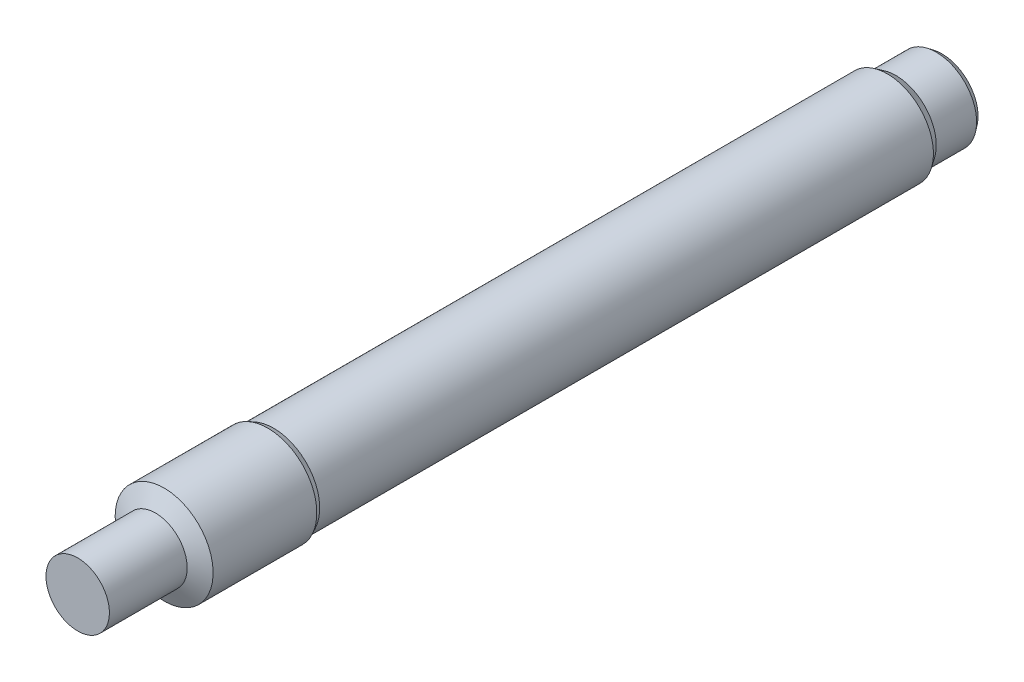
SolidWorks part; units mm, degrees
material "POM Acetal Copolymer"
ref_plane "Front Plane" through (0, 0, 0) normal (0, 0, 1) x (1, 0, 0)
ref_plane "Top Plane" through (0, 0, 0) normal (0, 1, 0) x (1, 0, 0)
ref_plane "Right Plane" through (0, 0, 0) normal (1, 0, 0) x (0, 0, -1)
sketch "Revolve profile 1" plane through (0, 0, 0) normal (0, 1, 0) x (1, 0, 0)
  line L0 (0, -300) -> (0, 0)
  line L1 (0, 0) -> (12.5, 0)
  line L2 (12.5, 0) -> (14, -2)
  line L3 (14, -2) -> (14, -16)
  line L4 (14, -16) -> (16, -19)
  line L5 (16, -19) -> (16, -232)
  line L6 (16, -232) -> (17, -234)
  line L7 (17, -234) -> (17, -270)
  line L8 (17, -270) -> (11, -273)
  line L9 (11, -273) -> (11, -300)
  line L10 (11, -300) -> (0, -300)
  line L11 (0, 5) -> (0, -305) construction
  dimension "D1" = 1
  dimension "D2" = 3
  dimension "D3" = 4.5
  dimension "D4" = 6
  dimension "D5" = 17
  dimension "D6" = 2
  dimension "D7" = 16
  dimension "D8" = 19
  dimension "D9" = 232
  dimension "D10" = 234
  dimension "D11" = 270
  dimension "D12" = 273
  dimension "D13" = 300
revolve "Revolve 1" add sketch "Revolve profile 1" angle 360 about L11
